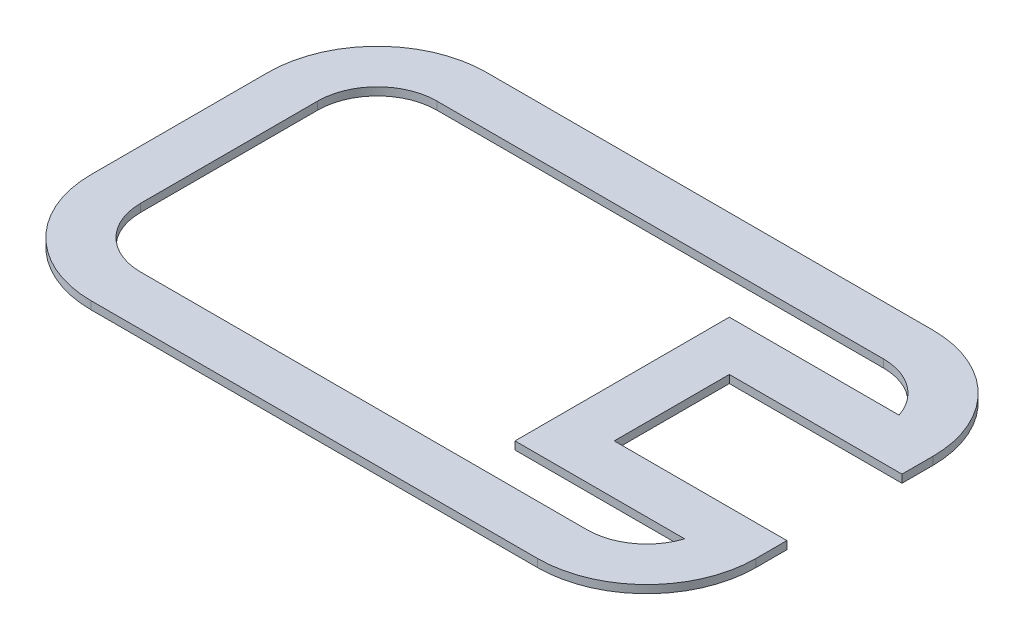
SolidWorks part; units mm, degrees
ref_plane "Front Plane" through (0, 0, 0) normal (0, 0, 1) x (1, 0, 0)
ref_plane "Top Plane" through (0, 0, 0) normal (0, 1, 0) x (1, 0, 0)
ref_plane "Right Plane" through (0, 0, 0) normal (1, 0, 0) x (0, 0, -1)
sketch "Sketch1" plane through (0, 0, 0) normal (0, 1, 0) x (1, 0, 0)
  line L0 (281.9923, -105.7816) -> (281.9923, -121.4116)
  line L1 (1.9623, 22.8484) -> (226.9923, 22.8484)
  line L2 (-53.0377, -32.1516) -> (-53.0377, -121.4116)
  line L3 (1.9623, -176.4116) -> (226.9923, -176.4116)
  line L4 (281.9923, -32.1516) -> (281.9923, -47.7816)
  line L5 (194.9923, -47.7816) -> (281.9923, -47.7816)
  line L6 (194.9923, -47.7816) -> (194.9923, -105.7816)
  line L7 (194.9923, -105.7816) -> (281.9923, -105.7816)
  line L8 (255.4915, -130.7816) -> (255.4915, -130.7816)
  line L9 (1.9623, -151.4116) -> (226.9923, -151.4116)
  line L10 (-28.0377, -32.1516) -> (-28.0377, -121.4116)
  line L11 (1.9623, -2.1516) -> (226.9923, -2.1516)
  line L12 (255.4915, -22.7816) -> (255.4915, -22.7816)
  line L13 (169.9923, -22.7816) -> (255.4915, -22.7816)
  line L14 (169.9923, -22.7816) -> (169.9923, -130.7816)
  line L15 (169.9923, -130.7816) -> (255.4915, -130.7816)
  arc A0 (-53.0377, -121.4116) -> (1.9623, -176.4116) centre (1.9623, -121.4116) ccw
  arc A1 (226.9923, -176.4116) -> (281.9923, -121.4116) centre (226.9923, -121.4116) ccw
  arc A2 (226.9923, 22.8484) -> (281.9923, -32.1516) centre (226.9923, -32.1516) cw
  arc A3 (1.9623, 22.8484) -> (-53.0377, -32.1516) centre (1.9623, -32.1516) ccw
  arc A4 (226.9923, -151.4116) -> (255.4915, -130.7816) centre (226.9923, -121.4116) ccw
  arc A5 (-28.0377, -121.4116) -> (1.9623, -151.4116) centre (1.9623, -121.4116) ccw
  arc A6 (1.9623, -2.1516) -> (-28.0377, -32.1516) centre (1.9623, -32.1516) ccw
  arc A7 (226.9923, -2.1516) -> (255.4915, -22.7816) centre (226.9923, -32.1516) cw
  point P6 (-53.0377, -176.4116)
  point P11 (281.9923, 22.8484)
  point P14 (-53.0377, 22.8484)
  dimension "D3" = 55
  dimension "D1" = 335.03
  dimension "D2" = 199.26
  dimension "D4" = 25
  dimension "D5" = 58
  dimension "D6" = 87
extrude "Boss-Extrude1" add sketch "Sketch1" along normal blind 4
